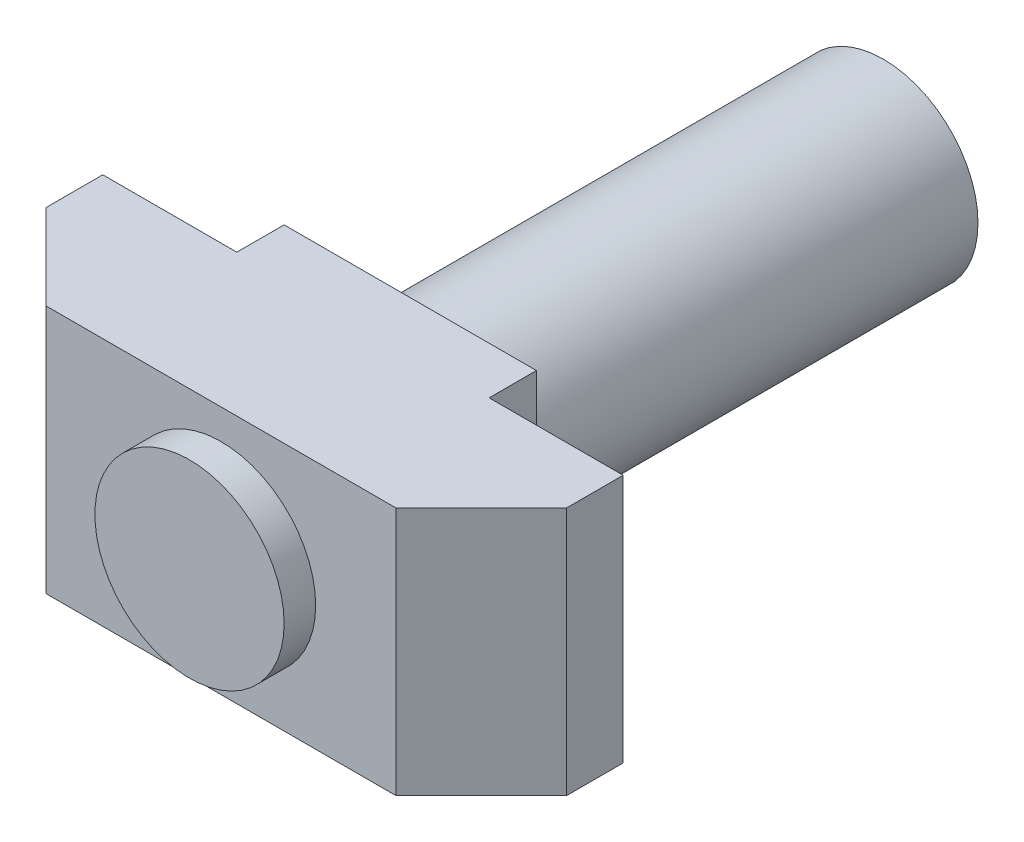
SolidWorks part; units mm, degrees
ref_plane "Front Plane" through (0, 0, 0) normal (0, 0, 1) x (1, 0, 0)
ref_plane "Top Plane" through (0, 0, 0) normal (0, 1, 0) x (1, 0, 0)
ref_plane "Right Plane" through (0, 0, 0) normal (1, 0, 0) x (0, 0, -1)
sketch "Sketch1" plane through (0, 0, 0) normal (0, 0, 1) x (1, 0, 0)
  circle A0 centre (0, 0) radius 3
  dimension "D1" = 6
extrude "Boss-Extrude1" add sketch "Sketch1" along normal blind 22
sketch "Sketch2" plane through (0, 0, 0) normal (0, 1, 0) x (1, 0, 0)
  line L0 (-5.55, -21) -> (-8.25, -18.3)
  line L1 (-8.25, -18.3) -> (-8.25, -16.5)
  line L2 (-8.25, -16.5) -> (-4, -16.5)
  line L3 (8.25, -16.5) -> (8.25, -18.3)
  line L4 (8.25, -18.3) -> (5.55, -21)
  line L5 (5.55, -21) -> (-5.55, -21)
  line L6 (-4, -16.5) -> (-4, -15)
  line L7 (-4, -15) -> (4, -15)
  line L8 (4, -15) -> (4, -16.5)
  line L9 (4, -16.5) -> (8.25, -16.5)
  line L10 (-3, 0) -> (-3, -22) construction
  line L11 (3, -22) -> (3, 0) construction
  line L12 (-3, 0) -> (-3, -22) construction
  line L13 (3, -22) -> (3, 0) construction
  line L14 (0, 0) -> (0, -22) construction
  line L15 (3, 0) -> (-3, 0) construction
  line L16 (-3, -22) -> (3, -22) construction
  point P20 (0, -15)
  point P21 (0, -11)
  dimension "D1" = 8
  dimension "D2" = 6
  dimension "D3" = 16.5
  dimension "D4" = 1.8
  dimension "D5" = 11.1
  dimension "D6" = 4
extrude "Boss-Extrude2" add sketch "Sketch2" along normal mid plane 7.9 contours L1 L2 L6 L7 L8 L9 L3 L4 L5 L0
